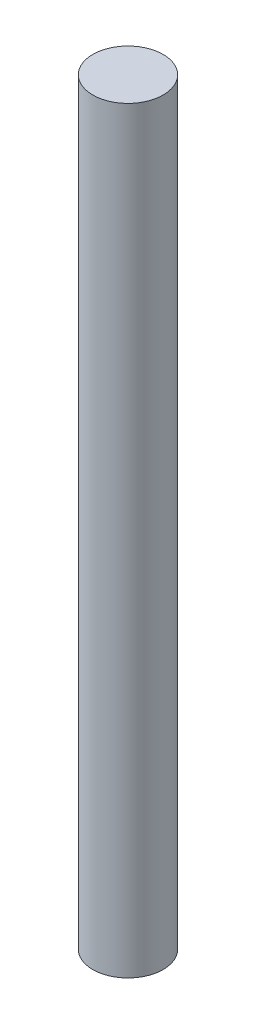
SolidWorks part; units mm, degrees
ref_plane "Piano frontale" through (0, 0, 0) normal (1, 0, 0) x (0, 1, 0)
ref_plane "Piano superiore" through (0, 0, 0) normal (0, 0, 1) x (0, 1, 0)
ref_plane "Piano destro" through (0, 0, 0) normal (0, 1, 0) x (-1, 0, 0)
sketch "Schizzo1" plane through (0, 0, 0) normal (0, 1, 0) x (-1, 0, 0)
  circle A0 centre (-48.5798, 412.0349) radius 309.25 construction
  circle A1 centre (-48.5798, 412.0349) radius 309.25
  circle A2 centre (-48.5798, 412.0349) radius 65
  dimension "D1" = 130
extrude "Estrusione-Estrusione1" add sketch "Schizzo1" along normal blind 700 contours A2
mirror "Specchia1" about plane through (0, 0, 0) normal (0, 1, 0) of bodies 101
